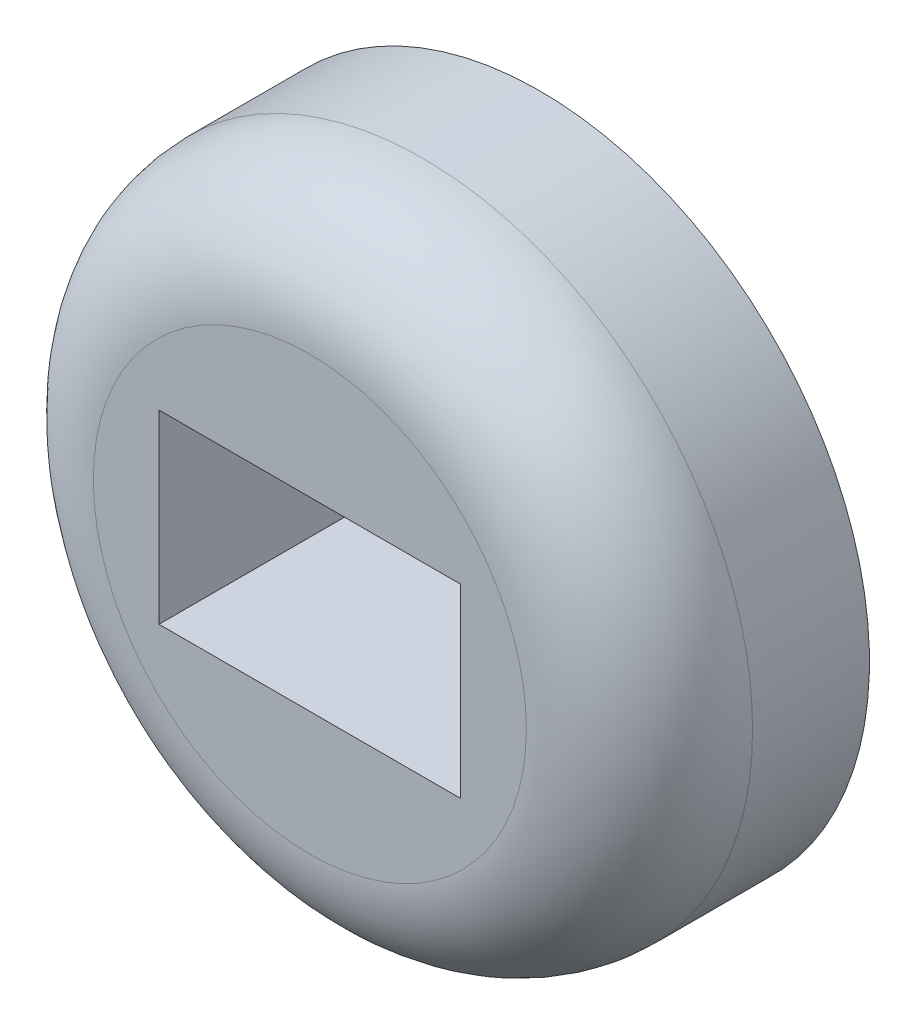
SolidWorks part; units mm, degrees
material "ABS"
ref_plane "Front Plane" through (0, 0, 0) normal (0, 0, 1) x (1, 0, 0)
ref_plane "Top Plane" through (0, 0, 0) normal (0, 1, 0) x (1, 0, 0)
ref_plane "Right Plane" through (0, 0, 0) normal (1, 0, 0) x (0, 0, -1)
sketch "Sketch1" plane through (0, 0, 0) normal (0, 0, 1) x (1, 0, 0)
  circle A0 centre (0, 0) radius 87.4196
  dimension "D1" = 174.8392
extrude "Boss-Extrude1" add sketch "Sketch1" along normal blind 61
fillet "Fillet1" radius 30 1 edges at (87.4196, 0, 61)
sketch "Sketch2" plane through (0, 0, 61) normal (0, 0, 1) x (1, 0, 0)
  line L1 (-40, 24.6) -> (40, 24.6)
  line L2 (-40, 24.6) -> (-40, -24.6)
  line L3 (-40, -24.6) -> (40, -24.6)
  line L4 (40, 24.6) -> (40, -24.6)
  line L5 (-40, 24.6) -> (40, -24.6) construction
  line L6 (-40, -24.6) -> (40, 24.6) construction
  point P0 (0, 0)
  dimension "D1" = 80
  dimension "D2" = 49.2
extrude "Cut-Extrude1" cut sketch "Sketch2" against normal blind 61 contours L2 L1 L4 L3
ref_plane "Midplane" through (0, 0, 30.5) normal (0, 0, 1) x (1, 0, 0)
